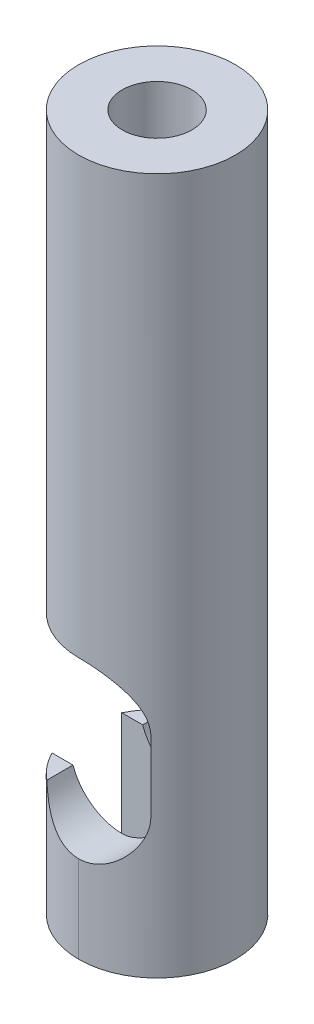
SolidWorks part; units mm, degrees
ref_plane "Front Plane" through (0, 0, 0) normal (0, 0, 1) x (1, 0, 0)
ref_plane "Top Plane" through (0, 0, 0) normal (0, 1, 0) x (1, 0, 0)
ref_plane "Right Plane" through (0, 0, 0) normal (1, 0, 0) x (0, 0, -1)
sketch "Sketch1" plane through (0, 0, 0) normal (0, 1, 0) x (1, 0, 0)
  circle A0 centre (0, 0) radius 2.54
  circle A1 centre (0, 0) radius 5.715
  dimension "D1" = 5.08
  dimension "D2" = 11.43
extrude "Boss-Extrude1" add sketch "Sketch1" along normal blind 50.8
sketch "Sketch3" plane through (0, 0, 0) normal (0, 0, 1) x (1, 0, 0)
  line L0 (0, 0) -> (0, 8.5633) construction
  line L1 (3.81, 15.24) -> (3.81, 10.16)
  line L2 (-3.81, 15.24) -> (-3.81, 10.16)
  arc A2 (-3.81, 10.16) -> (3.81, 10.16) centre (0, 10.16) ccw
  arc A3 (3.81, 15.24) -> (-3.81, 15.24) centre (0, 15.24) ccw
  point P5 (0, 0)
  point P13 (0, 0)
  point P14 (0, 0)
  dimension "D1" = 3.81
  dimension "D4" = 3.81
  dimension "D2" = 10.16
  dimension "D3" = 5.08
extrude "Cut-Extrude1" cut sketch "Sketch3" against normal through all both and the other way through all
sketch "Sketch4" plane through (0, 0, 0) normal (1, 0, 0) x (0, 0, -1)
  line L0 (-5.715, 19.05) -> (5.715, 19.05)
  line L1 (-5.715, 19.05) -> (-5.715, 8.89)
  line L2 (-5.715, 8.89) -> (5.715, 8.89)
  line L3 (5.715, 8.89) -> (5.715, 19.05)
  line L4 (-2.54, 8.89) -> (-2.54, 0)
  line L5 (-2.54, 0) -> (2.54, 0)
  line L6 (0, 6.2865) -> (0, -6.2865) construction
  line L7 (2.54, 8.89) -> (2.54, 0)
  spline S0 degree 2 poles (-5.715, 19.05) (-4.2597, 16.8671) (-4.2597, 15.24) knots 0 0 0 0.309017 0.309017 0.309017 weights 0.001905 0.003082 0.00426 construction
  spline S1 degree 2 poles (4.2597, 15.24) (4.2597, 16.8671) (5.715, 19.05) knots 0.309017 0.309017 0.309017 1 1 1 weights 0.00426 0.006892 0.009525 construction
  spline S2 degree 2 poles (-5.715, 19.05) (-4.2597, 16.8671) (-4.2597, 15.24) knots 0 0 0 0.309017 0.309017 0.309017 weights 0.001905 0.003082 0.00426
  spline S3 degree 2 poles (4.2597, 15.24) (4.2597, 16.8671) (5.715, 19.05) knots 0.309017 0.309017 0.309017 1 1 1 weights 0.00426 0.006892 0.009525
  point P14 (0, 0)
  point P17 (0, 0)
  dimension "D1" = 10.16
  dimension "D2" = 5.08
extrude "Cut-Extrude2" cut sketch "Sketch4" against normal blind 50.8
